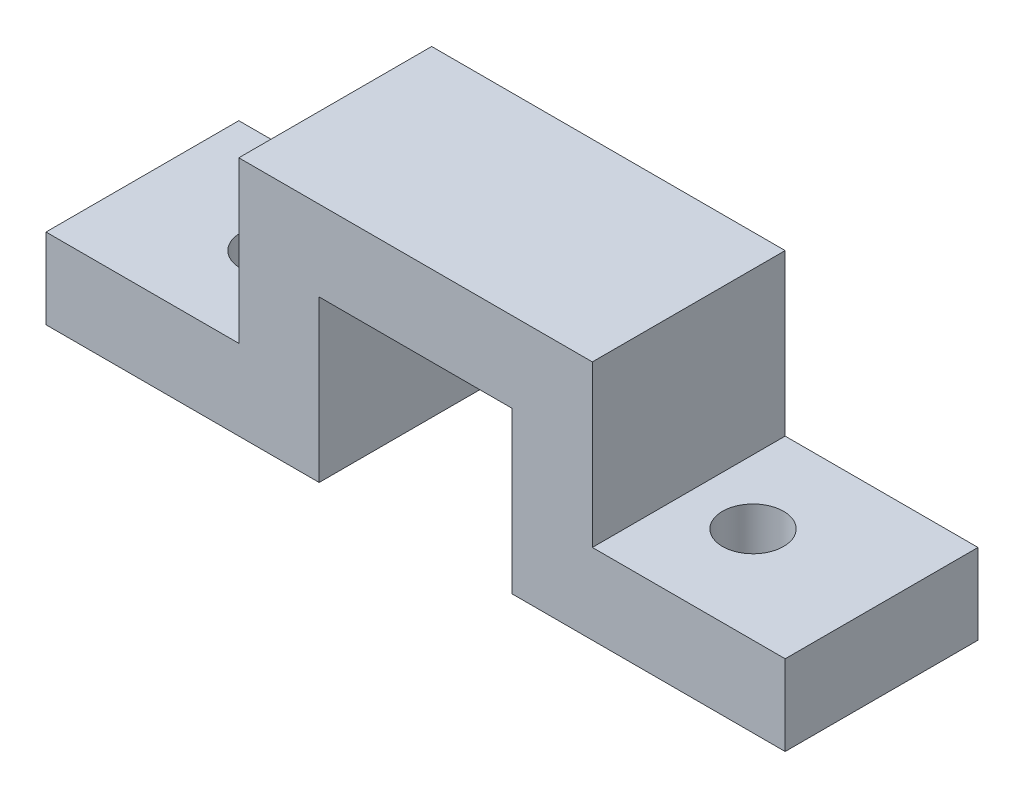
SolidWorks part; units mm, degrees
ref_plane "前视" through (0, 0, 0) normal (0, 0, 1) x (1, 0, 0)
ref_plane "上视" through (0, 0, 0) normal (0, 1, 0) x (1, 0, 0)
ref_plane "右视" through (0, 0, 0) normal (1, 0, 0) x (0, 0, -1)
sketch "草图1" plane through (0, 0, 0) normal (0, 0, 1) x (1, 0, 0)
  line L0 (0, 81.1666) -> (0, -66.8711) construction
  line L1 (15, 38.5978) -> (15, -32.2443) construction
  line L2 (-11, 15) -> (11, 15)
  line L3 (11, 15) -> (11, 5)
  line L4 (11, 5) -> (23, 5)
  line L5 (23, 5) -> (23, 0)
  line L6 (23, 0) -> (6, 0)
  line L7 (6, 0) -> (6, 10)
  line L8 (6, 10) -> (-6, 10)
  line L9 (-15, 38.5978) -> (-15, -32.2443) construction
  line L10 (-6, 0) -> (-6, 10)
  line L11 (-23, 0) -> (-6, 0)
  line L12 (-23, 5) -> (-23, 0)
  line L13 (-11, 5) -> (-23, 5)
  line L14 (-11, 15) -> (-11, 5)
  point P16 (0, 10)
  point P21 (0, 15)
  dimension "D1" = 5
  dimension "D2" = 5
  dimension "D3" = 5
  dimension "D4" = 15
  dimension "D5" = 10
  dimension "D6" = 12
  dimension "D7" = 6
extrude "凸台-拉伸1" add sketch "草图1" along normal blind 12
sketch "草图2" plane through (0, 0, 0) normal (0, 1, 0) x (1, 0, 0)
  line L2 (-15, 1.8076) -> (-15, -7.9) construction
  circle A0 centre (-15, -6) radius 1.9
  circle A1 centre (15, -6) radius 1.9
  dimension "D1" = 3.8
  dimension "D2" = 15
  dimension "D3" = 15
extrude "切除-拉伸5" cut sketch "草图2" along normal through all
